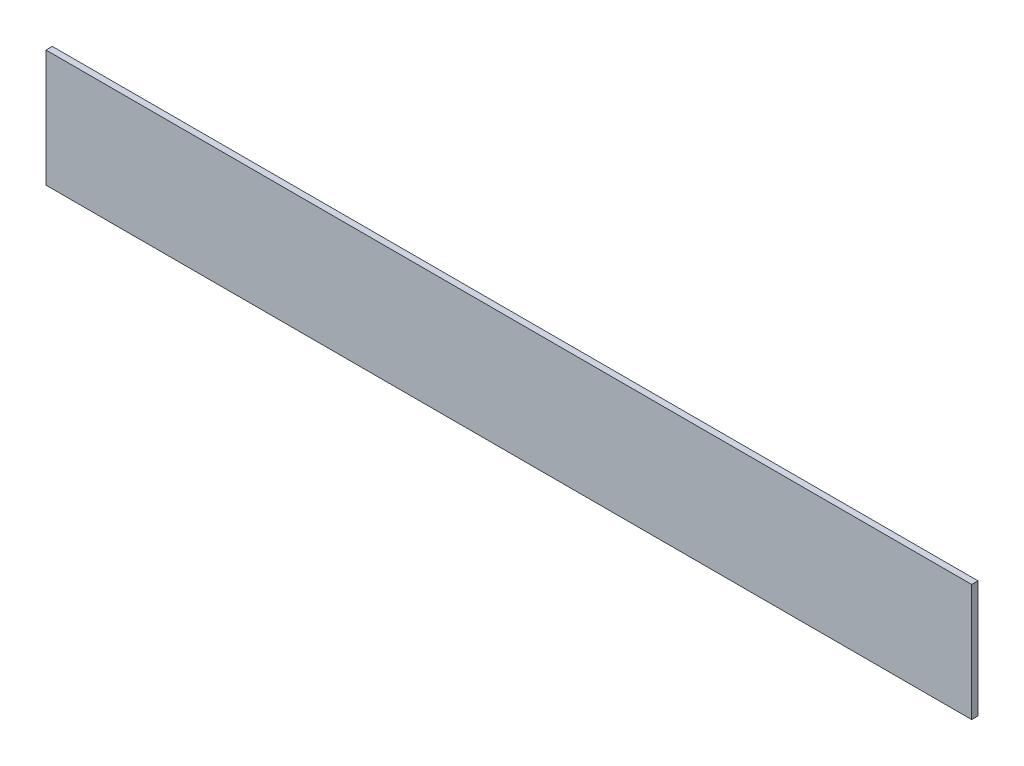
SolidWorks part; units mm, degrees
ref_plane "Alzado" through (0, 0, 0) normal (0, 0, 1) x (1, 0, 0)
ref_plane "Planta" through (0, 0, 0) normal (0, 1, 0) x (1, 0, 0)
ref_plane "Vista lateral" through (0, 0, 0) normal (1, 0, 0) x (0, 0, -1)
sketch "Croquis3" plane through (0, 0, 0) normal (0, 0, 1) x (1, 0, 0)
  line L1 (219.5, -27.75) -> (-219.5, -27.75)
  line L2 (219.5, -27.75) -> (219.5, 27.75)
  line L3 (219.5, 27.75) -> (-219.5, 27.75)
  line L4 (-219.5, -27.75) -> (-219.5, 27.75)
  line L5 (219.5, -27.75) -> (-219.5, 27.75) construction
  line L6 (219.5, 27.75) -> (-219.5, -27.75) construction
  point P0 (0, 0)
extrude "Saliente-Extruir3" add sketch "Croquis3" against normal blind 3
